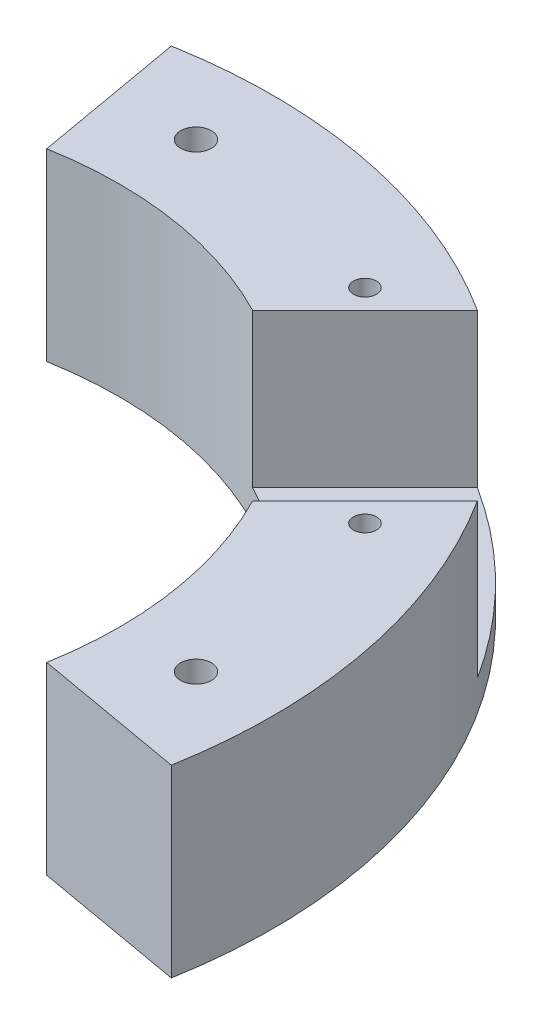
SolidWorks part; units mm, degrees
ref_plane "Front Plane" through (0, 0, 0) normal (0, 0, 1) x (1, 0, 0)
ref_plane "Top Plane" through (0, 0, 0) normal (0, 1, 0) x (1, 0, 0)
ref_plane "Right Plane" through (0, 0, 0) normal (1, 0, 0) x (0, 0, -1)
sketch "Sketch1" plane through (0, 0, 0) normal (0, 1, 0) x (1, 0, 0)
  line L0 (-10.853, 61.5505) -> (-15.1942, 86.1707)
  line L1 (61.5505, -10.853) -> (86.1707, -15.1942)
  line L2 (0, 0) -> (146.2995, -25.7965) construction
  line L3 (0, 0) -> (-22.8583, 129.6359) construction
  line L4 (0, 0) -> (-87.5, 0) construction
  circle A1 centre (75, 0) radius 2.5
  circle A2 centre (0, 75) radius 2.5
  circle A3 centre (0, 0) radius 87.5 construction
  circle A4 centre (0, 0) radius 62.5 construction
  arc A5 (61.5505, -10.853) -> (-10.853, 61.5505) centre (0, 0) ccw
  arc A6 (86.1707, -15.1942) -> (-15.1942, 86.1707) centre (0, 0) ccw
  dimension "D1" = 5
  dimension "D5" = 175
  dimension "D2" = 75
  dimension "D3" = 75
  dimension "D4" = 25
  dimension "D6" = 110
  dimension "D7" = 170
extrude "Boss-Extrude1" add sketch "Sketch1" along normal blind 30
sketch "Sketch2" plane through (0, 30, 0) normal (0, 1, 0) x (1, 0, 0)
  line L4 (28.6675, 55.5376) -> (46.9605, 73.8306)
  line L5 (55.5376, 28.6675) -> (73.8306, 46.9605)
  line L8 (8.8002, -18.0699) -> (26.8503, -0.0198) construction
  line L10 (-4.395, 22.4751) -> (-19.1196, 7.7504) construction
  line L11 (-4.3444, -4.3444) -> (34.5221, 34.5221) construction
  arc A3 (61.5505, -10.853) -> (-10.853, 61.5505) centre (0, 0) ccw construction
  arc A4 (86.1707, -15.1942) -> (-15.1942, 86.1707) centre (0, 0) ccw construction
  arc A5 (55.5376, 28.6675) -> (28.6675, 55.5376) centre (0, 0) ccw
  arc A6 (73.8306, 46.9605) -> (46.9605, 73.8306) centre (0, 0) ccw
  point P15 (37.814, 64.6841)
  point P16 (64.6841, 37.814)
  point P20 (44.1942, 44.1942)
  point P21 (44.1942, 44.1942)
  dimension "D1" = 38
extrude "Cut-Extrude1" cut sketch "Sketch2" against normal blind 25
sketch "Sketch3" plane through (0, 30, 0) normal (0, 1, 0) x (1, 0, 0)
  line L0 (-3.971, -3.971) -> (74.1405, 74.1405) construction
  line L1 (37.1363, 65.3618) -> (65.2253, 37.2728) construction
  line L4 (46.9605, 73.8306) -> (28.6675, 55.5376) construction
  line L5 (55.5376, 28.6675) -> (73.8306, 46.9605) construction
  circle A0 centre (67.8661, 34.6321) radius 1.875
  circle A1 centre (34.6321, 67.8661) radius 1.875
  arc A2 (55.5376, 28.6675) -> (28.6675, 55.5376) centre (0, 0) ccw construction
  point P10 (44.1942, 44.1942)
  point P13 (0, 0)
  point P14 (0, 0)
  point P17 (37.814, 64.6841)
  point P21 (64.6841, 37.814)
  dimension "D1" = 3.75
  dimension "D2" = 47
extrude "Cut-Extrude2" cut sketch "Sketch3" against normal through all
